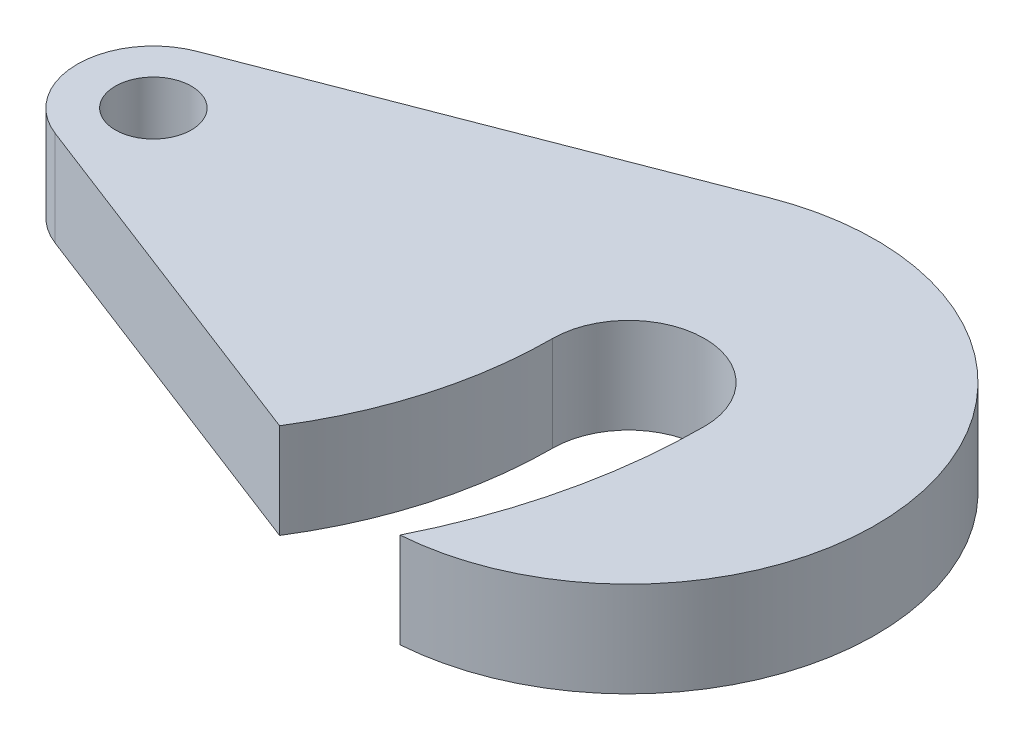
SolidWorks part; units mm, degrees
ref_plane "Front Plane" through (0, 0, 0) normal (0, 0, 1) x (1, 0, 0)
ref_plane "Top Plane" through (0, 0, 0) normal (0, 1, 0) x (1, 0, 0)
ref_plane "Right Plane" through (0, 0, 0) normal (1, 0, 0) x (0, 0, -1)
sketch "Sketch1" plane through (0, 0, 0) normal (0, 1, 0) x (1, 0, 0)
  line L0 (0, 0) -> (19216.6997, 0) construction
  line L1 (-2.88, 7.4636) -> (40.64, 24.2568)
  line L2 (-2.88, -7.4636) -> (35.5866, -22.3068)
  circle A0 centre (0, 0) radius 4
  arc A1 (-2.88, 7.4636) -> (-2.88, -7.4636) centre (0, 0) ccw
  arc A2 (50, 0) -> (30, -40) centre (0, 0) cw construction
  arc A3 (51.88, -25.9319) -> (58, 0) centre (0, 0) ccw
  arc A4 (35.5866, -22.3068) -> (42, 0) centre (0, 0) ccw
  arc A6 (58, 0) -> (42, 0) centre (50, 0) ccw
  arc A7 (51.88, -25.9319) -> (40.64, 24.2568) centre (50, 0) ccw
  point P5 (31.2208, -39.0546)
  dimension "D1" = 8
  dimension "D2" = 16
  dimension "D3" = 8
  dimension "D4" = 50
  dimension "D5" = 52
  dimension "D6" = 42
  dimension "D7" = 58
  dimension "D8" = 40
extrude "Boss-Extrude1" add sketch "Sketch1" along normal blind 10
sketch "Sketch2" plane through (0, 10, 0) normal (0, 1, 0) x (1, 0, 0)
  line L0 (30, 16) -> (30, -16) construction
  line L1 (0, 0) -> (50, 0) construction
  arc A0 (37.5, 0) -> (62.5, 0) centre (50, 0) cw construction
  circle A1 centre (0, 0) radius 4 construction
  text T0 "Sokolská L2B sk1"
  text T1 "Nosnost 20kg" font "Century Gothic" height 3.5
  point P8 (30, 0)
  point P12 (64.1432, 3.5191)
  point P13 (0, 0)
  point P14 (0, 0)
  dimension "D1" = 30
  dimension "D3" = 12.5
  dimension "D2" = 32
